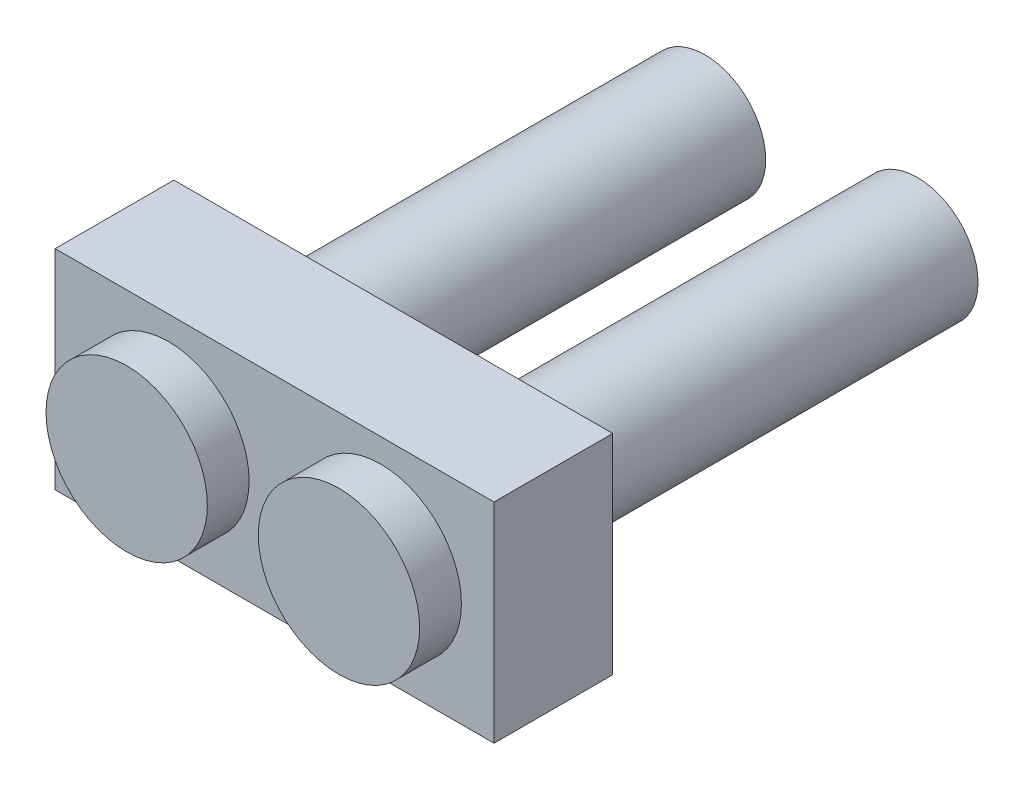
SolidWorks part; units mm, degrees
ref_plane "正面" through (0, 0, 0) normal (0, 0, 1) x (1, 0, 0)
ref_plane "平面" through (0, 0, 0) normal (0, 1, 0) x (1, 0, 0)
ref_plane "右側面" through (0, 0, 0) normal (1, 0, 0) x (0, 0, -1)
sketch "ｽｹｯﾁ1" plane through (0, 0, 0) normal (0, 0, 1) x (1, 0, 0)
  line L1 (2.625, -1.25) -> (-2.625, -1.25)
  line L2 (2.625, -1.25) -> (2.625, 1.25)
  line L3 (2.625, 1.25) -> (-2.625, 1.25)
  line L4 (-2.625, -1.25) -> (-2.625, 1.25)
  line L5 (2.625, -1.25) -> (-2.625, 1.25) construction
  line L6 (2.625, 1.25) -> (-2.625, -1.25) construction
  point P0 (0, 0)
  dimension "D1" = 5.25
  dimension "D2" = 2.5
extrude "ﾎﾞｽ - 押し出し1" add sketch "ｽｹｯﾁ1" along normal blind 1.42
sketch "ｽｹｯﾁ2" plane through (0, 0, 0) normal (0, 0, -1) x (-1, 0, 0)
  line L0 (0, 1.25) -> (0, -1.25) construction
  line L1 (-2.625, 1.25) -> (2.625, 1.25) construction
  line L2 (2.625, -1.25) -> (-2.625, -1.25) construction
  line L3 (-2.625, 0) -> (2.625, 0) construction
  line L4 (-2.625, -1.25) -> (-2.625, 1.25) construction
  line L5 (2.625, 1.25) -> (2.625, -1.25) construction
  circle A0 centre (-1.27, 0) radius 0.725
  circle A1 centre (1.27, 0) radius 0.725
  dimension "D1" = 1.45
  dimension "D2" = 1.27
extrude "ﾎﾞｽ - 押し出し2" add sketch "ｽｹｯﾁ2" along normal blind 5
sketch "ｽｹｯﾁ3" plane through (0, 0, 1.42) normal (0, 0, 1) x (1, 0, 0)
  circle A0 centre (-1.27, 0) radius 0.965
  circle A1 centre (1.27, 0) radius 0.965
  dimension "D1" = 1.93
extrude "ﾎﾞｽ - 押し出し3" add sketch "ｽｹｯﾁ3" along normal blind 0.5
